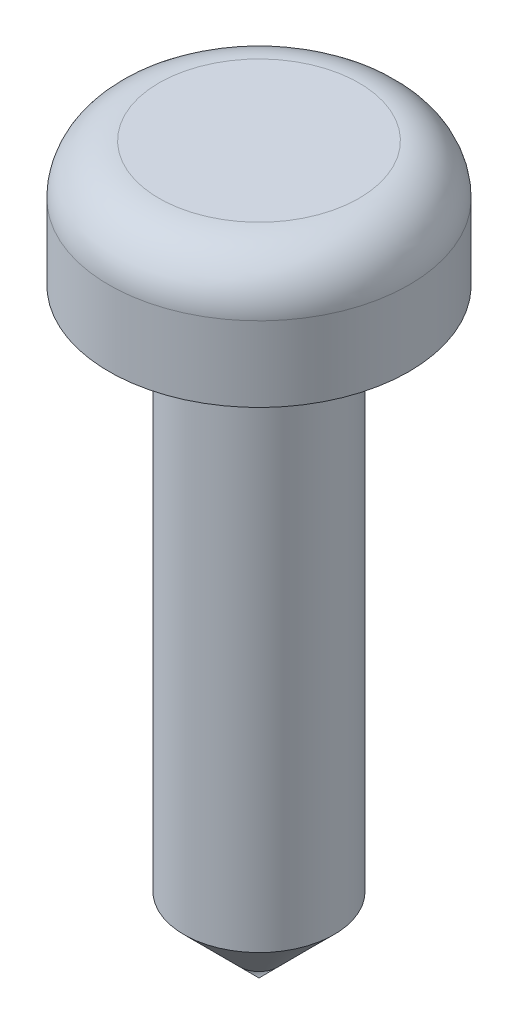
SolidWorks part; units mm, degrees
ref_plane "Front" through (0, 0, 0) normal (0, 0, 1) x (1, 0, 0)
ref_plane "Top" through (0, 0, 0) normal (0, 1, 0) x (1, 0, 0)
ref_plane "Right" through (0, 0, 0) normal (1, 0, 0) x (0, 0, -1)
sketch "Эскиз1" plane through (0, 0, 0) normal (0, 0, 1) x (1, 0, 0)
  line L0 (0, 14.5) -> (3, 14.5)
  line L1 (3, 14.5) -> (3, 12)
  line L2 (3, 12) -> (1.5, 12)
  line L3 (1.5, 12) -> (1.5, 1.5)
  line L4 (1.5, 1.5) -> (0, 0)
  line L5 (0, 14.5) -> (0, 0)
  dimension "D1" = 1.5
  dimension "D2" = 45
  dimension "D3" = 2.5
  dimension "D4" = 3
  dimension "D5" = 12
revolve "Шуруп М3х6" add sketch "Эскиз1" angle 360 about L5
fillet "Скругление1" radius 1 1 edges at (-3, 14.5, 0)
